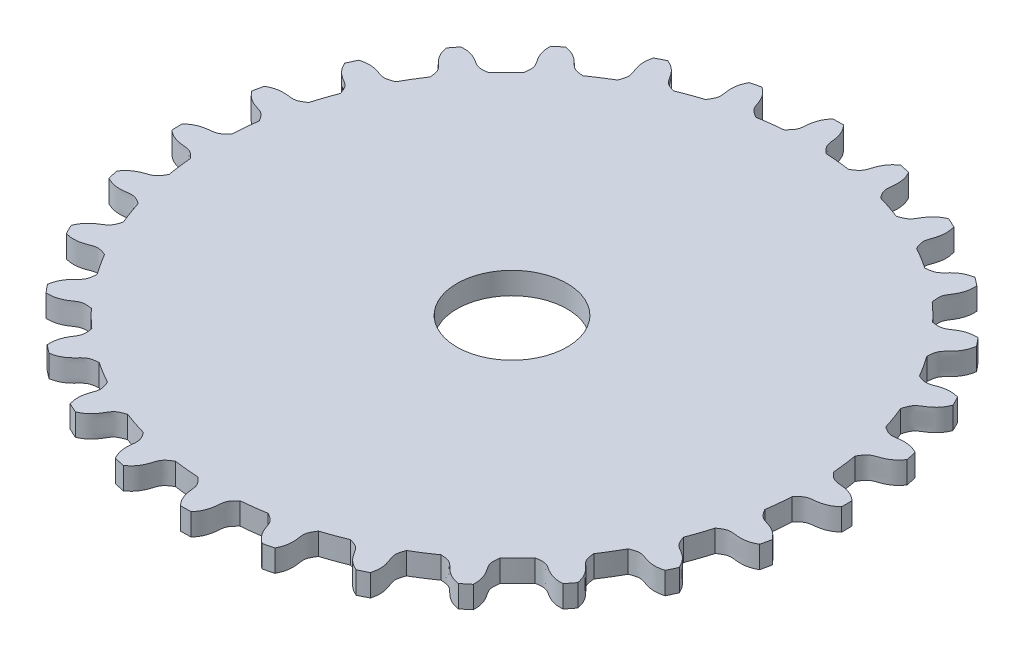
SolidWorks part; units mm, degrees
ref_plane "Front Plane" through (0, 0, 0) normal (0, 0, 1) x (1, 0, 0)
ref_plane "Top Plane" through (0, 0, 0) normal (0, 1, 0) x (1, 0, 0)
ref_plane "Right Plane" through (0, 0, 0) normal (1, 0, 0) x (0, 0, -1)
sketch "Sketch1" plane through (0, 0, 0) normal (0, 1, 0) x (1, 0, 0)
  circle A0 centre (0, 0) radius 30
  dimension "D1" = 60
extrude "Extrude1" add sketch "Sketch1" along normal blind 2
sketch "Sketch2" plane through (0, 2, 0) normal (0, 1, 0) x (1, 0, 0)
  circle A0 centre (0, 0) radius 5
  dimension "D1" = 10
extrude "Cut-Extrude1" cut sketch "Sketch2" against normal through all
sketch "Sketch3" plane through (0, 2, 0) normal (0, 1, 0) x (1, 0, 0)
  arc A0 (-13.7, 23.2661) -> (-15.6015, 22.0362) centre (0, 0) ccw
  arc A1 (-12.9355, 27.0679) -> (-13.8012, 26.6369) centre (0, 0) ccw
  arc A2 (-6.588, 29.2677) -> (-7.5279, 29.0402) centre (0, 0) ccw
  arc A3 (0.0899, 29.9999) -> (-0.8771, 29.9872) centre (0, 0) ccw
  arc A4 (6.7632, 29.2277) -> (5.8176, 29.4305) centre (0, 0) ccw
  arc A5 (13.0974, 26.99) -> (12.2207, 27.3981) centre (0, 0) ccw
  arc A6 (18.7749, 23.3988) -> (18.0109, 23.9918) centre (0, 0) ccw
  arc A7 (23.5109, 18.6344) -> (22.898, 19.3825) centre (0, 0) ccw
  arc A8 (27.0679, 12.9355) -> (26.6369, 13.8012) centre (0, 0) ccw
  arc A9 (29.2677, 6.588) -> (29.0402, 7.5279) centre (0, 0) ccw
  arc A10 (29.9999, -0.0899) -> (29.9872, 0.8771) centre (0, 0) ccw
  arc A11 (29.2277, -6.7632) -> (29.4305, -5.8176) centre (0, 0) ccw
  arc A12 (26.99, -13.0974) -> (27.3981, -12.2207) centre (0, 0) ccw
  arc A13 (23.3988, -18.7749) -> (23.9918, -18.0109) centre (0, 0) ccw
  arc A14 (18.6344, -23.5109) -> (19.3825, -22.898) centre (0, 0) ccw
  arc A15 (12.9355, -27.0679) -> (13.8012, -26.6369) centre (0, 0) ccw
  arc A16 (6.588, -29.2677) -> (7.5279, -29.0402) centre (0, 0) ccw
  arc A17 (-0.0899, -29.9999) -> (0.8771, -29.9872) centre (0, 0) ccw
  arc A18 (-6.7632, -29.2277) -> (-5.8176, -29.4305) centre (0, 0) ccw
  arc A19 (-13.0974, -26.99) -> (-12.2207, -27.3981) centre (0, 0) ccw
  arc A20 (-18.7749, -23.3988) -> (-18.0109, -23.9918) centre (0, 0) ccw
  arc A21 (-23.5109, -18.6344) -> (-22.898, -19.3825) centre (0, 0) ccw
  arc A22 (-27.0679, -12.9355) -> (-26.6369, -13.8012) centre (0, 0) ccw
  arc A23 (-29.2677, -6.588) -> (-29.0402, -7.5279) centre (0, 0) ccw
  arc A24 (-29.9999, 0.0899) -> (-29.9872, -0.8771) centre (0, 0) ccw
  arc A25 (-29.2277, 6.7632) -> (-29.4305, 5.8176) centre (0, 0) ccw
  arc A26 (-26.99, 13.0974) -> (-27.3981, 12.2207) centre (0, 0) ccw
  arc A27 (-23.3988, 18.7749) -> (-23.9918, 18.0109) centre (0, 0) ccw
  arc A28 (-18.6344, 23.5109) -> (-19.3825, 22.898) centre (0, 0) ccw
  arc A29 (-8.1793, 25.7313) -> (-10.3068, 24.9554) centre (0, 0) ccw
  arc A30 (-2.2485, 26.9062) -> (-4.4953, 26.6232) centre (0, 0) ccw
  arc A31 (9.6483, 25.2173) -> (7.5012, 25.9371) centre (0, 0) ccw
  arc A32 (15.0178, 22.4381) -> (13.0847, 23.6176) centre (0, 0) ccw
  arc A33 (19.6342, 18.5337) -> (18.012, 20.1138) centre (0, 0) ccw
  arc A34 (23.2661, 13.7) -> (22.0362, 15.6015) centre (0, 0) ccw
  arc A35 (25.7313, 8.1793) -> (24.9554, 10.3068) centre (0, 0) ccw
  arc A36 (26.9062, 2.2485) -> (26.6232, 4.4953) centre (0, 0) ccw
  arc A37 (26.732, -3.795) -> (26.956, -1.5416) centre (0, 0) ccw
  arc A38 (25.2173, -9.6483) -> (25.9371, -7.5012) centre (0, 0) ccw
  arc A39 (22.4381, -15.0178) -> (23.6176, -13.0847) centre (0, 0) ccw
  arc A40 (18.5337, -19.6342) -> (20.1138, -18.012) centre (0, 0) ccw
  arc A41 (13.7, -23.2661) -> (15.6015, -22.0362) centre (0, 0) ccw
  arc A42 (8.1793, -25.7313) -> (10.3068, -24.9554) centre (0, 0) ccw
  arc A43 (2.2485, -26.9062) -> (4.4953, -26.6232) centre (0, 0) ccw
  arc A44 (-3.795, -26.732) -> (-1.5416, -26.956) centre (0, 0) ccw
  arc A45 (-9.6483, -25.2173) -> (-7.5012, -25.9371) centre (0, 0) ccw
  arc A46 (-15.0178, -22.4381) -> (-13.0847, -23.6176) centre (0, 0) ccw
  arc A47 (-19.6342, -18.5337) -> (-18.012, -20.1138) centre (0, 0) ccw
  arc A48 (-23.2661, -13.7) -> (-22.0362, -15.6015) centre (0, 0) ccw
  arc A49 (-25.7313, -8.1793) -> (-24.9554, -10.3068) centre (0, 0) ccw
  arc A50 (-26.9062, -2.2485) -> (-26.6232, -4.4953) centre (0, 0) ccw
  arc A51 (-26.732, 3.795) -> (-26.956, 1.5416) centre (0, 0) ccw
  arc A52 (-25.2173, 9.6483) -> (-25.9371, 7.5012) centre (0, 0) ccw
  arc A53 (-22.4381, 15.0178) -> (-23.6176, 13.0847) centre (0, 0) ccw
  arc A54 (-18.5337, 19.6342) -> (-20.1138, 18.012) centre (0, 0) ccw
  arc A55 (3.795, 26.732) -> (1.5416, 26.956) centre (0, 0) ccw
  spline S0 degree 3 poles (-13.8012, 26.6369) (-13.8412, 26.4498) (-13.9602, 25.8932) (-13.823, 25.0442) (-13.377, 24.1438) (-13.5882, 23.57) (-13.7, 23.2661) knots 0 0 0 0 0.165713 0.492772 0.731383 1 1 1 1
  spline S1 degree 3 poles (-12.9355, 27.0679) (-12.762, 26.9871) (-12.2462, 26.7466) (-11.6515, 26.1252) (-11.2019, 25.2267) (-10.6167, 25.0493) (-10.3068, 24.9554) knots 0 0 0 0 0.165713 0.492772 0.731383 1 1 1 1
  spline S2 degree 3 poles (-7.5279, 29.0402) (-7.6086, 28.8666) (-7.8484, 28.3505) (-7.9035, 27.4922) (-7.6691, 26.5151) (-8.0027, 26.0027) (-8.1793, 25.7313) knots 0 0 0 0 0.165713 0.492772 0.731383 1 1 1 1
  spline S3 degree 3 poles (-6.588, 29.2677) (-6.4369, 29.1503) (-5.9875, 28.801) (-5.546, 28.0629) (-5.3075, 27.0868) (-4.7765, 26.7837) (-4.4953, 26.6232) knots 0 0 0 0 0.165713 0.492772 0.731383 1 1 1 1
  spline S4 degree 3 poles (-0.8771, 29.9872) (-0.9944, 29.8359) (-1.3431, 29.3861) (-1.5878, 28.5616) (-1.5767, 27.5569) (-2.0159, 27.1315) (-2.2485, 26.9062) knots 0 0 0 0 0.165713 0.492772 0.731383 1 1 1 1
  spline S5 degree 3 poles (0.0899, 29.9999) (0.211, 29.8517) (0.5714, 29.4113) (0.8377, 28.5934) (0.8529, 27.5888) (1.3032, 27.175) (1.5416, 26.956) knots 0 0 0 0 0.165713 0.492772 0.731383 1 1 1 1
  spline S6 degree 3 poles (5.8176, 29.4305) (5.6696, 29.3091) (5.2296, 28.9482) (4.8076, 28.1988) (4.5948, 27.2168) (4.072, 26.8998) (3.795, 26.732) knots 0 0 0 0 0.165713 0.492772 0.731383 1 1 1 1
  spline S7 degree 3 poles (6.7632, 29.2277) (6.8484, 29.0563) (7.1017, 28.5467) (7.1793, 27.6901) (6.9706, 26.7073) (7.3175, 26.2037) (7.5012, 25.9371) knots 0 0 0 0 0.165713 0.492772 0.731383 1 1 1 1
  spline S8 degree 3 poles (12.2207, 27.3981) (12.0494, 27.3127) (11.5401, 27.0587) (10.9619, 26.422) (10.5359, 25.512) (9.9556, 25.3193) (9.6483, 25.2173) knots 0 0 0 0 0.165713 0.492772 0.731383 1 1 1 1
  spline S9 degree 3 poles (13.0974, 26.99) (13.1423, 26.8039) (13.2759, 26.2507) (13.1609, 25.3983) (12.7388, 24.4865) (12.9649, 23.9184) (13.0847, 23.6176) knots 0 0 0 0 0.165713 0.492772 0.731383 1 1 1 1
  spline S10 degree 3 poles (18.0109, 23.9918) (17.8249, 23.9467) (17.2719, 23.8124) (16.5665, 23.3203) (15.9487, 22.5279) (15.3401, 22.4691) (15.0178, 22.4381) knots 0 0 0 0 0.165713 0.492772 0.731383 1 1 1 1
  spline S11 degree 3 poles (18.7749, 23.3988) (18.7773, 23.2074) (18.7844, 22.6384) (18.4826, 21.833) (17.8681, 21.038) (17.9622, 20.4338) (18.012, 20.1138) knots 0 0 0 0 0.165713 0.492772 0.731383 1 1 1 1
  spline S12 degree 3 poles (22.898, 19.3825) (22.7067, 19.3798) (22.1376, 19.372) (21.3404, 19.0493) (20.5618, 18.4141) (19.9553, 18.4923) (19.6342, 18.5337) knots 0 0 0 0 0.165713 0.492772 0.731383 1 1 1 1
  spline S13 degree 3 poles (23.5109, 18.6344) (23.4706, 18.4473) (23.3509, 17.8909) (22.8775, 17.1728) (22.1015, 16.5345) (22.0588, 15.9245) (22.0362, 15.6015) knots 0 0 0 0 0.165713 0.492772 0.731383 1 1 1 1
  spline S14 degree 3 poles (26.6369, 13.8012) (26.4498, 13.8412) (25.8932, 13.9602) (25.0442, 13.823) (24.1438, 13.377) (23.57, 13.5882) (23.2661, 13.7) knots 0 0 0 0 0.165713 0.492772 0.731383 1 1 1 1
  spline S15 degree 3 poles (27.0679, 12.9355) (26.9871, 12.762) (26.7466, 12.2462) (26.1252, 11.6515) (25.2267, 11.2019) (25.0493, 10.6167) (24.9554, 10.3068) knots 0 0 0 0 0.165713 0.492772 0.731383 1 1 1 1
  spline S16 degree 3 poles (29.0402, 7.5279) (28.8666, 7.6086) (28.3505, 7.8484) (27.4922, 7.9035) (26.5151, 7.6691) (26.0027, 8.0027) (25.7313, 8.1793) knots 0 0 0 0 0.165713 0.492772 0.731383 1 1 1 1
  spline S17 degree 3 poles (29.2677, 6.588) (29.1503, 6.4369) (28.801, 5.9875) (28.0629, 5.546) (27.0868, 5.3075) (26.7837, 4.7765) (26.6232, 4.4953) knots 0 0 0 0 0.165713 0.492772 0.731383 1 1 1 1
  spline S18 degree 3 poles (29.9872, 0.8771) (29.8359, 0.9944) (29.3861, 1.3431) (28.5616, 1.5878) (27.5569, 1.5767) (27.1315, 2.0159) (26.9062, 2.2485) knots 0 0 0 0 0.165713 0.492772 0.731383 1 1 1 1
  spline S19 degree 3 poles (29.9999, -0.0899) (29.8517, -0.211) (29.4113, -0.5714) (28.5934, -0.8377) (27.5888, -0.8529) (27.175, -1.3032) (26.956, -1.5416) knots 0 0 0 0 0.165713 0.492772 0.731383 1 1 1 1
  spline S20 degree 3 poles (29.4305, -5.8176) (29.3091, -5.6696) (28.9482, -5.2296) (28.1988, -4.8076) (27.2168, -4.5948) (26.8998, -4.072) (26.732, -3.795) knots 0 0 0 0 0.165713 0.492772 0.731383 1 1 1 1
  spline S21 degree 3 poles (29.2277, -6.7632) (29.0563, -6.8484) (28.5467, -7.1017) (27.6901, -7.1793) (26.7073, -6.9706) (26.2037, -7.3175) (25.9371, -7.5012) knots 0 0 0 0 0.165713 0.492772 0.731383 1 1 1 1
  spline S22 degree 3 poles (27.3981, -12.2207) (27.3127, -12.0494) (27.0587, -11.5401) (26.422, -10.9619) (25.512, -10.5359) (25.3193, -9.9556) (25.2173, -9.6483) knots 0 0 0 0 0.165713 0.492772 0.731383 1 1 1 1
  spline S23 degree 3 poles (26.99, -13.0974) (26.8039, -13.1423) (26.2507, -13.2759) (25.3983, -13.1609) (24.4865, -12.7388) (23.9184, -12.9649) (23.6176, -13.0847) knots 0 0 0 0 0.165713 0.492772 0.731383 1 1 1 1
  spline S24 degree 3 poles (23.9918, -18.0109) (23.9467, -17.8249) (23.8124, -17.2719) (23.3203, -16.5665) (22.5279, -15.9487) (22.4691, -15.3401) (22.4381, -15.0178) knots 0 0 0 0 0.165713 0.492772 0.731383 1 1 1 1
  spline S25 degree 3 poles (23.3988, -18.7749) (23.2074, -18.7773) (22.6384, -18.7844) (21.833, -18.4826) (21.038, -17.8681) (20.4338, -17.9622) (20.1138, -18.012) knots 0 0 0 0 0.165713 0.492772 0.731383 1 1 1 1
  spline S26 degree 3 poles (19.3825, -22.898) (19.3798, -22.7067) (19.372, -22.1376) (19.0493, -21.3404) (18.4141, -20.5618) (18.4923, -19.9553) (18.5337, -19.6342) knots 0 0 0 0 0.165713 0.492772 0.731383 1 1 1 1
  spline S27 degree 3 poles (18.6344, -23.5109) (18.4473, -23.4706) (17.8909, -23.3509) (17.1728, -22.8775) (16.5345, -22.1015) (15.9245, -22.0588) (15.6015, -22.0362) knots 0 0 0 0 0.165713 0.492772 0.731383 1 1 1 1
  spline S28 degree 3 poles (13.8012, -26.6369) (13.8412, -26.4498) (13.9602, -25.8932) (13.823, -25.0442) (13.377, -24.1438) (13.5882, -23.57) (13.7, -23.2661) knots 0 0 0 0 0.165713 0.492772 0.731383 1 1 1 1
  spline S29 degree 3 poles (12.9355, -27.0679) (12.762, -26.9871) (12.2462, -26.7466) (11.6515, -26.1252) (11.2019, -25.2267) (10.6167, -25.0493) (10.3068, -24.9554) knots 0 0 0 0 0.165713 0.492772 0.731383 1 1 1 1
  spline S30 degree 3 poles (7.5279, -29.0402) (7.6086, -28.8666) (7.8484, -28.3505) (7.9035, -27.4922) (7.6691, -26.5151) (8.0027, -26.0027) (8.1793, -25.7313) knots 0 0 0 0 0.165713 0.492772 0.731383 1 1 1 1
  spline S31 degree 3 poles (6.588, -29.2677) (6.4369, -29.1503) (5.9875, -28.801) (5.546, -28.0629) (5.3075, -27.0868) (4.7765, -26.7837) (4.4953, -26.6232) knots 0 0 0 0 0.165713 0.492772 0.731383 1 1 1 1
  spline S32 degree 3 poles (0.8771, -29.9872) (0.9944, -29.8359) (1.3431, -29.3861) (1.5878, -28.5616) (1.5767, -27.5569) (2.0159, -27.1315) (2.2485, -26.9062) knots 0 0 0 0 0.165713 0.492772 0.731383 1 1 1 1
  spline S33 degree 3 poles (-0.0899, -29.9999) (-0.211, -29.8517) (-0.5714, -29.4113) (-0.8377, -28.5934) (-0.8529, -27.5888) (-1.3032, -27.175) (-1.5416, -26.956) knots 0 0 0 0 0.165713 0.492772 0.731383 1 1 1 1
  spline S34 degree 3 poles (-5.8176, -29.4305) (-5.6696, -29.3091) (-5.2296, -28.9482) (-4.8076, -28.1988) (-4.5948, -27.2168) (-4.072, -26.8998) (-3.795, -26.732) knots 0 0 0 0 0.165713 0.492772 0.731383 1 1 1 1
  spline S35 degree 3 poles (-6.7632, -29.2277) (-6.8484, -29.0563) (-7.1017, -28.5467) (-7.1793, -27.6901) (-6.9706, -26.7073) (-7.3175, -26.2037) (-7.5012, -25.9371) knots 0 0 0 0 0.165713 0.492772 0.731383 1 1 1 1
  spline S36 degree 3 poles (-12.2207, -27.3981) (-12.0494, -27.3127) (-11.5401, -27.0587) (-10.9619, -26.422) (-10.5359, -25.512) (-9.9556, -25.3193) (-9.6483, -25.2173) knots 0 0 0 0 0.165713 0.492772 0.731383 1 1 1 1
  spline S37 degree 3 poles (-13.0974, -26.99) (-13.1423, -26.8039) (-13.2759, -26.2507) (-13.1609, -25.3983) (-12.7388, -24.4865) (-12.9649, -23.9184) (-13.0847, -23.6176) knots 0 0 0 0 0.165713 0.492772 0.731383 1 1 1 1
  spline S38 degree 3 poles (-18.0109, -23.9918) (-17.8249, -23.9467) (-17.2719, -23.8124) (-16.5665, -23.3203) (-15.9487, -22.5279) (-15.3401, -22.4691) (-15.0178, -22.4381) knots 0 0 0 0 0.165713 0.492772 0.731383 1 1 1 1
  spline S39 degree 3 poles (-18.7749, -23.3988) (-18.7773, -23.2074) (-18.7844, -22.6384) (-18.4826, -21.833) (-17.8681, -21.038) (-17.9622, -20.4338) (-18.012, -20.1138) knots 0 0 0 0 0.165713 0.492772 0.731383 1 1 1 1
  spline S40 degree 3 poles (-22.898, -19.3825) (-22.7067, -19.3798) (-22.1376, -19.372) (-21.3404, -19.0493) (-20.5618, -18.4141) (-19.9553, -18.4923) (-19.6342, -18.5337) knots 0 0 0 0 0.165713 0.492772 0.731383 1 1 1 1
  spline S41 degree 3 poles (-23.5109, -18.6344) (-23.4706, -18.4473) (-23.3509, -17.8909) (-22.8775, -17.1728) (-22.1015, -16.5345) (-22.0588, -15.9245) (-22.0362, -15.6015) knots 0 0 0 0 0.165713 0.492772 0.731383 1 1 1 1
  spline S42 degree 3 poles (-26.6369, -13.8012) (-26.4498, -13.8412) (-25.8932, -13.9602) (-25.0442, -13.823) (-24.1438, -13.377) (-23.57, -13.5882) (-23.2661, -13.7) knots 0 0 0 0 0.165713 0.492772 0.731383 1 1 1 1
  spline S43 degree 3 poles (-27.0679, -12.9355) (-26.9871, -12.762) (-26.7466, -12.2462) (-26.1252, -11.6515) (-25.2267, -11.2019) (-25.0493, -10.6167) (-24.9554, -10.3068) knots 0 0 0 0 0.165713 0.492772 0.731383 1 1 1 1
  spline S44 degree 3 poles (-29.0402, -7.5279) (-28.8666, -7.6086) (-28.3505, -7.8484) (-27.4922, -7.9035) (-26.5151, -7.6691) (-26.0027, -8.0027) (-25.7313, -8.1793) knots 0 0 0 0 0.165713 0.492772 0.731383 1 1 1 1
  spline S45 degree 3 poles (-29.2677, -6.588) (-29.1503, -6.4369) (-28.801, -5.9875) (-28.0629, -5.546) (-27.0868, -5.3075) (-26.7837, -4.7765) (-26.6232, -4.4953) knots 0 0 0 0 0.165713 0.492772 0.731383 1 1 1 1
  spline S46 degree 3 poles (-29.9872, -0.8771) (-29.8359, -0.9944) (-29.3861, -1.3431) (-28.5616, -1.5878) (-27.5569, -1.5767) (-27.1315, -2.0159) (-26.9062, -2.2485) knots 0 0 0 0 0.165713 0.492772 0.731383 1 1 1 1
  spline S47 degree 3 poles (-29.9999, 0.0899) (-29.8517, 0.211) (-29.4113, 0.5714) (-28.5934, 0.8377) (-27.5888, 0.8529) (-27.175, 1.3032) (-26.956, 1.5416) knots 0 0 0 0 0.165713 0.492772 0.731383 1 1 1 1
  spline S48 degree 3 poles (-29.4305, 5.8176) (-29.3091, 5.6696) (-28.9482, 5.2296) (-28.1988, 4.8076) (-27.2168, 4.5948) (-26.8998, 4.072) (-26.732, 3.795) knots 0 0 0 0 0.165713 0.492772 0.731383 1 1 1 1
  spline S49 degree 3 poles (-29.2277, 6.7632) (-29.0563, 6.8484) (-28.5467, 7.1017) (-27.6901, 7.1793) (-26.7073, 6.9706) (-26.2037, 7.3175) (-25.9371, 7.5012) knots 0 0 0 0 0.165713 0.492772 0.731383 1 1 1 1
  spline S50 degree 3 poles (-27.3981, 12.2207) (-27.3127, 12.0494) (-27.0587, 11.5401) (-26.422, 10.9619) (-25.512, 10.5359) (-25.3193, 9.9556) (-25.2173, 9.6483) knots 0 0 0 0 0.165713 0.492772 0.731383 1 1 1 1
  spline S51 degree 3 poles (-26.99, 13.0974) (-26.8039, 13.1423) (-26.2507, 13.2759) (-25.3983, 13.1609) (-24.4865, 12.7388) (-23.9184, 12.9649) (-23.6176, 13.0847) knots 0 0 0 0 0.165713 0.492772 0.731383 1 1 1 1
  spline S52 degree 3 poles (-23.9918, 18.0109) (-23.9467, 17.8249) (-23.8124, 17.2719) (-23.3203, 16.5665) (-22.5279, 15.9487) (-22.4691, 15.3401) (-22.4381, 15.0178) knots 0 0 0 0 0.165713 0.492772 0.731383 1 1 1 1
  spline S53 degree 3 poles (-23.3988, 18.7749) (-23.2074, 18.7773) (-22.6384, 18.7844) (-21.833, 18.4826) (-21.038, 17.8681) (-20.4338, 17.9622) (-20.1138, 18.012) knots 0 0 0 0 0.165713 0.492772 0.731383 1 1 1 1
  spline S54 degree 3 poles (-19.3825, 22.898) (-19.3798, 22.7067) (-19.372, 22.1376) (-19.0493, 21.3404) (-18.4141, 20.5618) (-18.4923, 19.9553) (-18.5337, 19.6342) knots 0 0 0 0 0.165713 0.492772 0.731383 1 1 1 1
  spline S55 degree 3 poles (-18.6344, 23.5109) (-18.4473, 23.4706) (-17.8909, 23.3509) (-17.1728, 22.8775) (-16.5345, 22.1015) (-15.9245, 22.0588) (-15.6015, 22.0362) knots 0 0 0 0 0.165713 0.492772 0.731383 1 1 1 1
  circle M6 centre (0, 0) radius 30
extrude "Cut-Extrude5" cut sketch "Sketch3" against normal through all contours S48 S47 A51 M6 | S50 S49 A52 M6 | S52 S51 A53 M6 | S54 S53 A54 M6 | S55 A0 S0 M6 | S2 S1 A29 M6 | S4 S3 A30 M6 | S6 S5 A55 M6 | S8 S7 A31 M6 | S10 S9 A32 M6 | S12 S11 A33 M6 | S14 S13 A34 M6 | S16 S15 A35 M6 | S18 S17 A36 M6 | S20 S19 A37 M6 | S22 S21 A38 M6 | S24 S23 A39 M6 | S26 S25 A40 M6 | S28 S27 A41 M6 | S30 S29 A42 M6 | S32 S31 A43 M6 | S34 S33 A44 M6 | S36 S35 A45 M6 | S38 S37 A46 M6 | S40 S39 A47 M6 | S42 S41 A48 M6 | S44 S43 A49 M6 | S46 S45 A50 M6
